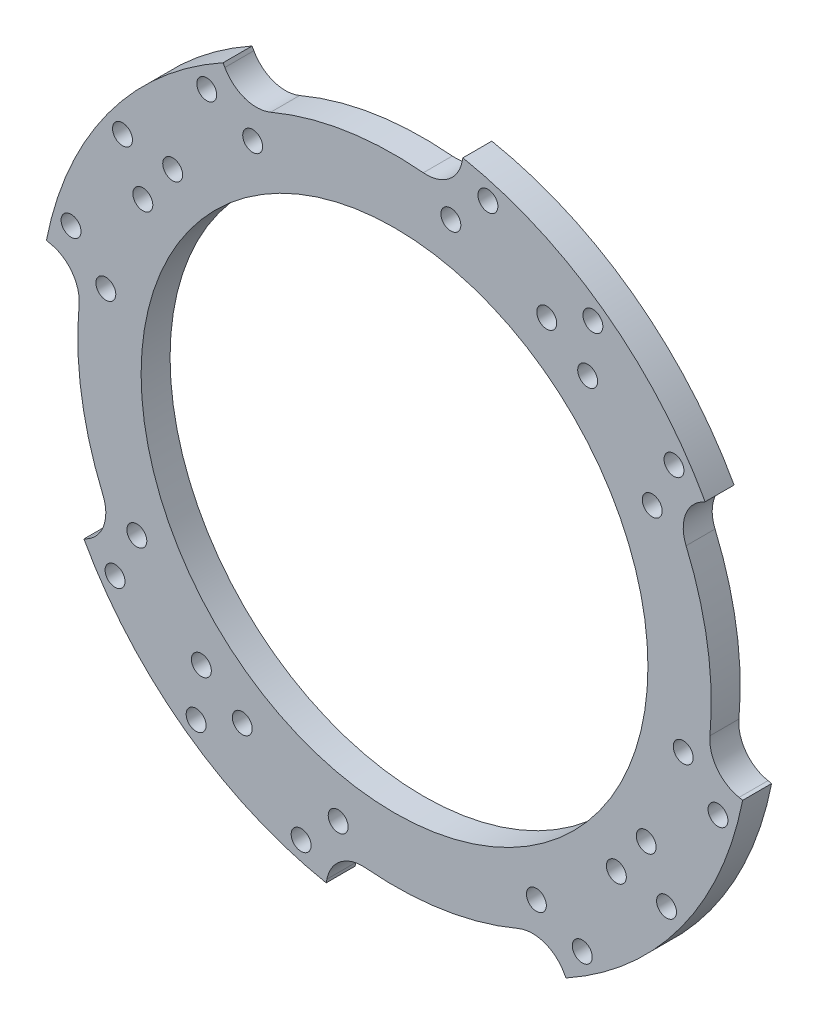
SolidWorks part; units mm, degrees
ref_plane "前视基准面" through (0, 0, 0) normal (0, 0, 1) x (1, 0, 0)
ref_plane "上视基准面" through (0, 0, 0) normal (0, 1, 0) x (1, 0, 0)
ref_plane "右视基准面" through (0, 0, 0) normal (1, 0, 0) x (0, 0, -1)
sketch "草图1" plane through (0, 0, 0) normal (0, 0, 1) x (1, 0, 0)
  circle A0 centre (0, 0) radius 70
  circle A1 centre (0, 0) radius 87.5
  dimension "D1" = 140
  dimension "D2" = 175
extrude "凸台-拉伸1" add sketch "草图1" along normal blind 8
sketch "草图2" plane through (0, 0, 8) normal (0, 0, 1) x (1, 0, 0)
  circle A0 centre (0, 0) radius 81.25 construction
  circle A2 centre (42.0516, 69.5214) radius 2.75
  circle A3 centre (53.352, 61.2791) radius 2.75
  circle A4 centre (71.1784, 39.1816) radius 2.75
  circle A6 centre (15.5646, 79.7452) radius 2.75
  dimension "D1" = 162.5
  dimension "D2" = 5.5
extrude "切除-拉伸1" cut sketch "草图2" against normal blind 10
pattern_circular "阵列(圆周)1" count 4 over 360 about axis through (0, 0, 0) along (0, 0, 1) of "切除-拉伸1"
sketch "草图3" plane through (0, 0, 8) normal (0, 0, 1) x (1, 0, 0)
  line L0 (0, 0) -> (-71.1784, -39.1816) construction
  line L1 (0, 0) -> (-89.3496, 25.8001) construction
  line L2 (0, 0) -> (-129.4054, -20.2497) construction
  line L3 (0, 0) -> (-19.2768, 123.1882) construction
  line L4 (0, 0) -> (-104.6553, 76.3337) construction
  line L5 (-42.2787, 76.6078) -> (-47.3522, 85.8008)
  line L6 (-85.8612, 16.8552) -> (-96.1646, 18.8778)
  arc A0 (-42.2787, 76.6078) -> (-85.8612, 16.8552) centre (0, 0) ccw
  arc A1 (-47.3522, 85.8008) -> (-96.1646, 18.8778) centre (0, 0) ccw
  circle A2 centre (0, 0) radius 93 construction
  circle A3 centre (-89.3496, 25.8001) radius 2.75
  circle A4 centre (-51.8618, 77.1969) radius 2.75
  circle A5 centre (-75.137, 54.8036) radius 2.75
  circle A6 centre (0, 0) radius 87.5 construction
  dimension "D4" = 98
  dimension "D5" = 186
  dimension "D6" = 5.5
  dimension "D1" = 45
  dimension "D2" = 25
  dimension "D3" = 25
  dimension "D7" = 20
extrude "凸台-拉伸2" add sketch "草图3" against normal up to surface (8 mm away) up to face at (-76.9952, 15.5646, 0)
pattern_circular "阵列(圆周)2" count 4 over 360 about axis through (0, 0, 0) along (0, 0, 1) of "凸台-拉伸2"
fillet "圆角1" radius 10 8 edges at (-76.6078, -42.2787, 4) (-85.8612, 16.8552, 4) (-16.8552, -85.8612, 4) (42.2787, -76.6078, 4) (85.8612, -16.8552, 4) (76.6078, 42.2787, 4) (16.8552, 85.8612, 4) (-42.2787, 76.6078, 4)
